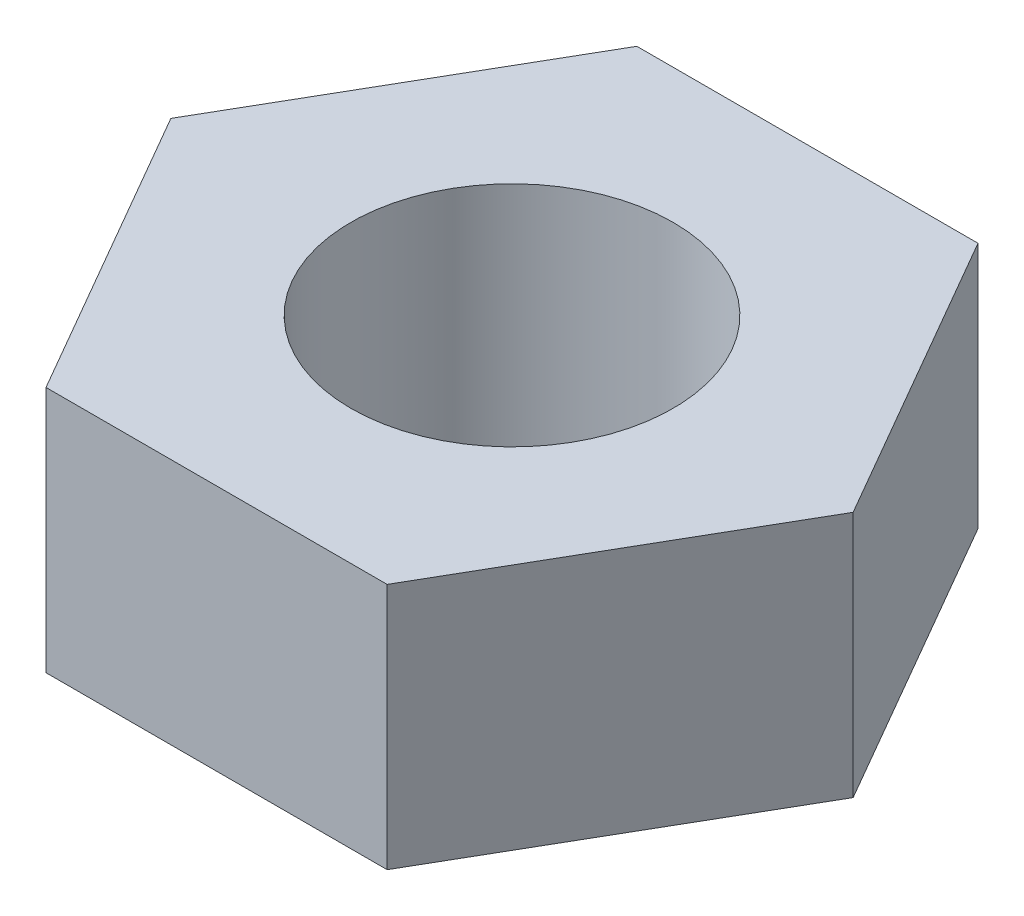
SolidWorks part; units mm, degrees
material "1060 Alloy"
ref_plane "Front Plane" through (0, 0, 0) normal (0, 0, 1) x (1, 0, 0)
ref_plane "Top Plane" through (0, 0, 0) normal (0, 1, 0) x (1, 0, 0)
ref_plane "Right Plane" through (0, 0, 0) normal (1, 0, 0) x (0, 0, -1)
sketch "Sketch1" plane through (0, 0, 0) normal (0, 1, 0) x (1, 0, 0)
  line L1 (3.1754, 0) -> (1.5877, 2.75)
  line L2 (1.5877, 2.75) -> (-1.5877, 2.75)
  line L3 (-1.5877, 2.75) -> (-3.1754, 0)
  line L4 (-3.1754, 0) -> (-1.5877, -2.75)
  line L5 (-1.5877, -2.75) -> (1.5877, -2.75)
  line L6 (1.5877, -2.75) -> (3.1754, 0)
  circle A0 centre (0, 0) radius 2.75 construction
  circle A1 centre (0, 0) radius 1.5
  dimension "D1" = 5.5
  dimension "D2" = 3
extrude "Boss-Extrude1" add sketch "Sketch1" along normal blind 2.3
